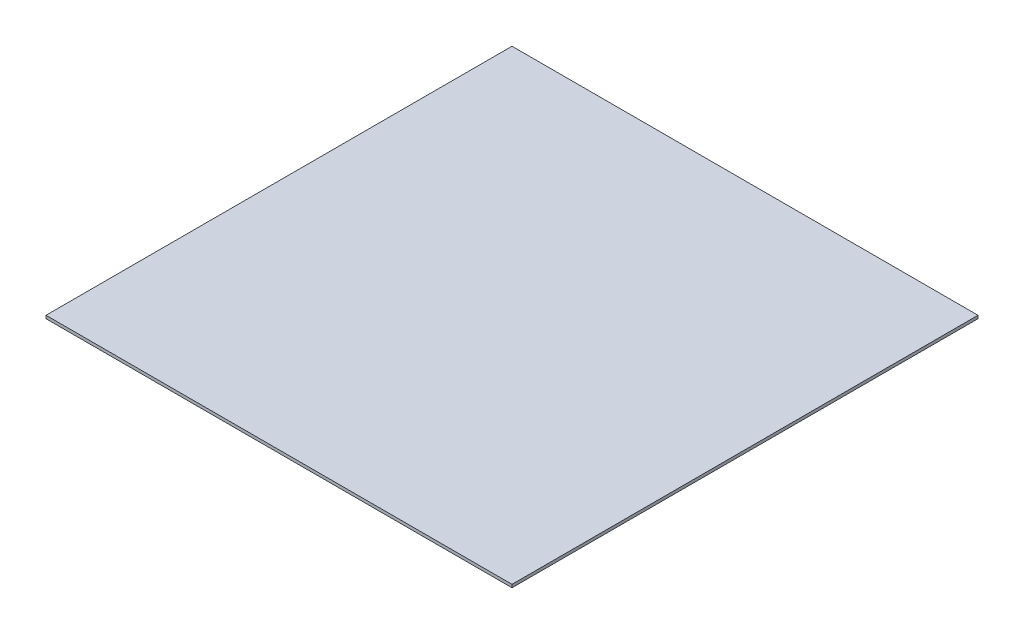
SolidWorks part; units mm, degrees
ref_plane "Front Plane" through (0, 0, 0) normal (0, 0, 1) x (1, 0, 0)
ref_plane "Top Plane" through (0, 0, 0) normal (0, 1, 0) x (1, 0, 0)
ref_plane "Right Plane" through (0, 0, 0) normal (1, 0, 0) x (0, 0, -1)
sketch "Sketch1" plane through (0, 0, 0) normal (0, 1, 0) x (1, 0, 0)
  line L1 (-155, 155) -> (155, 155)
  line L2 (-155, 155) -> (-155, -155)
  line L3 (-155, -155) -> (155, -155)
  line L4 (155, 155) -> (155, -155)
  line L5 (-155, 155) -> (155, -155) construction
  line L6 (-155, -155) -> (155, 155) construction
  point P0 (0, 0)
  dimension "D1" = 310
  dimension "D2" = 310
extrude "Boss-Extrude1" add sketch "Sketch1" along normal blind 2
